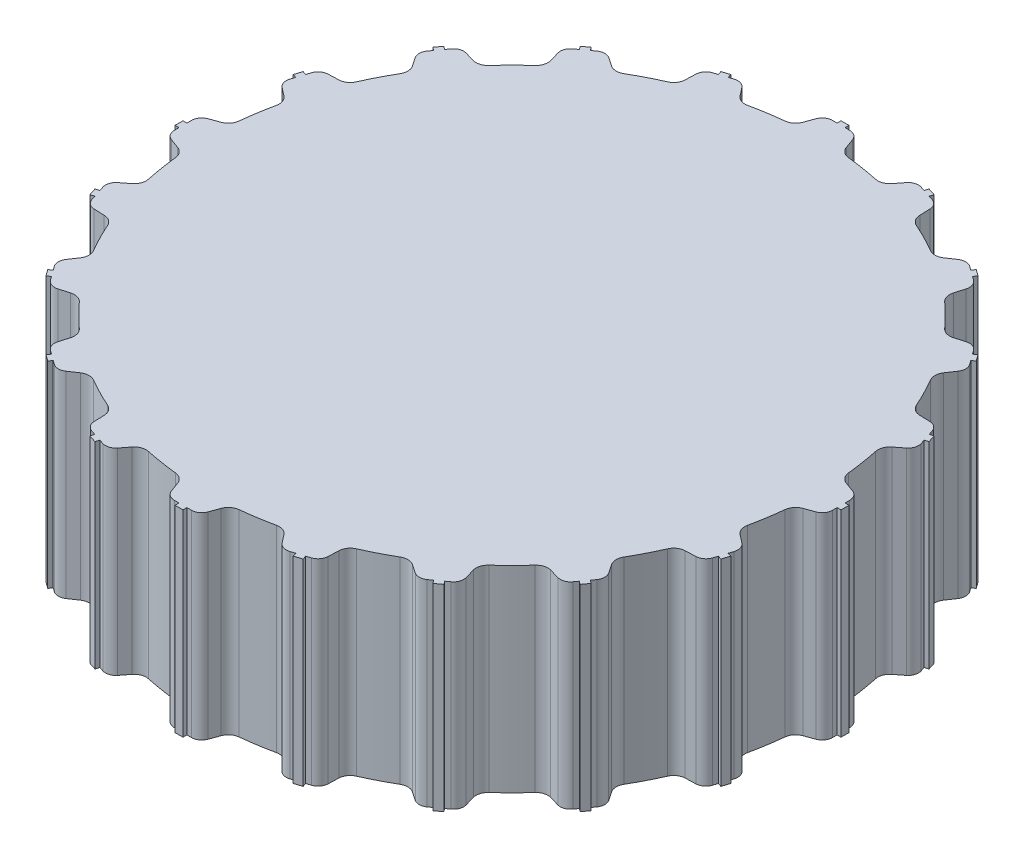
SolidWorks part; units mm, degrees
ref_plane "Front Plane" through (0, 0, 0) normal (0, 0, 1) x (1, 0, 0)
ref_plane "Top Plane" through (0, 0, 0) normal (0, 1, 0) x (1, 0, 0)
ref_plane "Right Plane" through (0, 0, 0) normal (1, 0, 0) x (0, 0, -1)
sketch "Sketch1" plane through (0, 0, 0) normal (0, 1, 0) x (1, 0, 0)
  line L0 (0, 0) -> (0, -23.4605) construction
  line L1 (-0.4359, -16.71) -> (-0.2, -16.71)
  line L2 (0.9245, -16.3679) -> (1.1054, -15.871)
  line L3 (1.2368, -15.51) -> (-2.616, -15.51) construction
  line L4 (0, -15.51) -> (2.4735, -15.51) construction
  line L5 (0.2, -16.71) -> (0.2, -16.91)
  line L6 (0.2, -16.91) -> (-0.2, -16.91)
  line L7 (-0.2, -16.71) -> (-0.2, -16.91)
  line L8 (-0.9245, -16.3679) -> (-1.1054, -15.871)
  line L9 (0.2, -16.71) -> (0.4359, -16.71)
  line L10 (-5.5782, -15.7575) -> (-5.3539, -15.8304)
  line L11 (-5.9372, -15.2811) -> (-5.9557, -14.7526)
  line L12 (-5.3539, -15.8304) -> (-5.4157, -16.0206)
  line L13 (-5.0353, -16.1442) -> (-5.4157, -16.0206)
  line L14 (-4.9735, -15.954) -> (-5.0353, -16.1442)
  line L15 (-4.9735, -15.954) -> (-4.7491, -16.0269)
  line L16 (-4.1787, -15.8524) -> (-3.8531, -15.4358)
  line L17 (-10.1745, -13.2625) -> (-9.9837, -13.4011)
  line L18 (-10.3687, -12.6984) -> (-10.223, -12.1902)
  line L19 (-9.9837, -13.4011) -> (-10.1013, -13.5629)
  line L20 (-9.7776, -13.798) -> (-10.1013, -13.5629)
  line L21 (-9.6601, -13.6362) -> (-9.7776, -13.798)
  line L22 (-9.6601, -13.6362) -> (-9.4692, -13.7749)
  line L23 (-8.8728, -13.7853) -> (-8.4345, -13.4896)
  line L24 (-13.7749, -9.4692) -> (-13.6362, -9.6601)
  line L25 (-13.7853, -8.8728) -> (-13.4896, -8.4345)
  line L26 (-13.6362, -9.6601) -> (-13.798, -9.7776)
  line L27 (-13.5629, -10.1013) -> (-13.798, -9.7776)
  line L28 (-13.4011, -9.9837) -> (-13.5629, -10.1013)
  line L29 (-13.4011, -9.9837) -> (-13.2625, -10.1745)
  line L30 (-12.6984, -10.3687) -> (-12.1902, -10.223)
  line L31 (-16.0269, -4.7491) -> (-15.954, -4.9735)
  line L32 (-15.8524, -4.1787) -> (-15.4358, -3.8531)
  line L33 (-15.954, -4.9735) -> (-16.1442, -5.0353)
  line L34 (-16.0206, -5.4157) -> (-16.1442, -5.0353)
  line L35 (-15.8304, -5.3539) -> (-16.0206, -5.4157)
  line L36 (-15.8304, -5.3539) -> (-15.7575, -5.5782)
  line L37 (-15.2811, -5.9372) -> (-14.7526, -5.9557)
  line L38 (-16.71, 0.4359) -> (-16.71, 0.2)
  line L39 (-16.3679, 0.9245) -> (-15.871, 1.1054)
  line L40 (-16.71, 0.2) -> (-16.91, 0.2)
  line L41 (-16.91, -0.2) -> (-16.91, 0.2)
  line L42 (-16.71, -0.2) -> (-16.91, -0.2)
  line L43 (-16.71, -0.2) -> (-16.71, -0.4359)
  line L44 (-16.3679, -0.9245) -> (-15.871, -1.1054)
  line L45 (-15.7575, 5.5782) -> (-15.8304, 5.3539)
  line L46 (-15.2811, 5.9372) -> (-14.7526, 5.9557)
  line L47 (-15.8304, 5.3539) -> (-16.0206, 5.4157)
  line L48 (-16.1442, 5.0353) -> (-16.0206, 5.4157)
  line L49 (-15.954, 4.9735) -> (-16.1442, 5.0353)
  line L50 (-15.954, 4.9735) -> (-16.0269, 4.7491)
  line L51 (-15.8524, 4.1787) -> (-15.4358, 3.8531)
  line L52 (-13.2625, 10.1745) -> (-13.4011, 9.9837)
  line L53 (-12.6984, 10.3687) -> (-12.1902, 10.223)
  line L54 (-13.4011, 9.9837) -> (-13.5629, 10.1013)
  line L55 (-13.798, 9.7776) -> (-13.5629, 10.1013)
  line L56 (-13.6362, 9.6601) -> (-13.798, 9.7776)
  line L57 (-13.6362, 9.6601) -> (-13.7749, 9.4692)
  line L58 (-13.7853, 8.8728) -> (-13.4896, 8.4345)
  line L59 (-9.4692, 13.7749) -> (-9.6601, 13.6362)
  line L60 (-8.8728, 13.7853) -> (-8.4345, 13.4896)
  line L61 (-9.6601, 13.6362) -> (-9.7776, 13.798)
  line L62 (-10.1013, 13.5629) -> (-9.7776, 13.798)
  line L63 (-9.9837, 13.4011) -> (-10.1013, 13.5629)
  line L64 (-9.9837, 13.4011) -> (-10.1745, 13.2625)
  line L65 (-10.3687, 12.6984) -> (-10.223, 12.1902)
  line L66 (-4.7491, 16.0269) -> (-4.9735, 15.954)
  line L67 (-4.1787, 15.8524) -> (-3.8531, 15.4358)
  line L68 (-4.9735, 15.954) -> (-5.0353, 16.1442)
  line L69 (-5.4157, 16.0206) -> (-5.0353, 16.1442)
  line L70 (-5.3539, 15.8304) -> (-5.4157, 16.0206)
  line L71 (-5.3539, 15.8304) -> (-5.5782, 15.7575)
  line L72 (-5.9372, 15.2811) -> (-5.9557, 14.7526)
  line L73 (0.4359, 16.71) -> (0.2, 16.71)
  line L74 (0.9245, 16.3679) -> (1.1054, 15.871)
  line L75 (0.2, 16.71) -> (0.2, 16.91)
  line L76 (-0.2, 16.91) -> (0.2, 16.91)
  line L77 (-0.2, 16.71) -> (-0.2, 16.91)
  line L78 (-0.2, 16.71) -> (-0.4359, 16.71)
  line L79 (-0.9245, 16.3679) -> (-1.1054, 15.871)
  line L80 (5.5782, 15.7575) -> (5.3539, 15.8304)
  line L81 (5.9372, 15.2811) -> (5.9557, 14.7526)
  line L82 (5.3539, 15.8304) -> (5.4157, 16.0206)
  line L83 (5.0353, 16.1442) -> (5.4157, 16.0206)
  line L84 (4.9735, 15.954) -> (5.0353, 16.1442)
  line L85 (4.9735, 15.954) -> (4.7491, 16.0269)
  line L86 (4.1787, 15.8524) -> (3.8531, 15.4358)
  line L87 (10.1745, 13.2625) -> (9.9837, 13.4011)
  line L88 (10.3687, 12.6984) -> (10.223, 12.1902)
  line L89 (9.9837, 13.4011) -> (10.1013, 13.5629)
  line L90 (9.7776, 13.798) -> (10.1013, 13.5629)
  line L91 (9.6601, 13.6362) -> (9.7776, 13.798)
  line L92 (9.6601, 13.6362) -> (9.4692, 13.7749)
  line L93 (8.8728, 13.7853) -> (8.4345, 13.4896)
  line L94 (13.7749, 9.4692) -> (13.6362, 9.6601)
  line L95 (13.7853, 8.8728) -> (13.4896, 8.4345)
  line L96 (13.6362, 9.6601) -> (13.798, 9.7776)
  line L97 (13.5629, 10.1013) -> (13.798, 9.7776)
  line L98 (13.4011, 9.9837) -> (13.5629, 10.1013)
  line L99 (13.4011, 9.9837) -> (13.2625, 10.1745)
  line L100 (12.6984, 10.3687) -> (12.1902, 10.223)
  line L101 (16.0269, 4.7491) -> (15.954, 4.9735)
  line L102 (15.8524, 4.1787) -> (15.4358, 3.8531)
  line L103 (15.954, 4.9735) -> (16.1442, 5.0353)
  line L104 (16.0206, 5.4157) -> (16.1442, 5.0353)
  line L105 (15.8304, 5.3539) -> (16.0206, 5.4157)
  line L106 (15.8304, 5.3539) -> (15.7575, 5.5782)
  line L107 (15.2811, 5.9372) -> (14.7526, 5.9557)
  line L108 (16.71, -0.4359) -> (16.71, -0.2)
  line L109 (16.3679, -0.9245) -> (15.871, -1.1054)
  line L110 (16.71, -0.2) -> (16.91, -0.2)
  line L111 (16.91, 0.2) -> (16.91, -0.2)
  line L112 (16.71, 0.2) -> (16.91, 0.2)
  line L113 (16.71, 0.2) -> (16.71, 0.4359)
  line L114 (16.3679, 0.9245) -> (15.871, 1.1054)
  line L115 (15.7575, -5.5782) -> (15.8304, -5.3539)
  line L116 (15.2811, -5.9372) -> (14.7526, -5.9557)
  line L117 (15.8304, -5.3539) -> (16.0206, -5.4157)
  line L118 (16.1442, -5.0353) -> (16.0206, -5.4157)
  line L119 (15.954, -4.9735) -> (16.1442, -5.0353)
  line L120 (15.954, -4.9735) -> (16.0269, -4.7491)
  line L121 (15.8524, -4.1787) -> (15.4358, -3.8531)
  line L122 (13.2625, -10.1745) -> (13.4011, -9.9837)
  line L123 (12.6984, -10.3687) -> (12.1902, -10.223)
  line L124 (13.4011, -9.9837) -> (13.5629, -10.1013)
  line L125 (13.798, -9.7776) -> (13.5629, -10.1013)
  line L126 (13.6362, -9.6601) -> (13.798, -9.7776)
  line L127 (13.6362, -9.6601) -> (13.7749, -9.4692)
  line L128 (13.7853, -8.8728) -> (13.4896, -8.4345)
  line L129 (9.4692, -13.7749) -> (9.6601, -13.6362)
  line L130 (8.8728, -13.7853) -> (8.4345, -13.4896)
  line L131 (9.6601, -13.6362) -> (9.7776, -13.798)
  line L132 (10.1013, -13.5629) -> (9.7776, -13.798)
  line L133 (9.9837, -13.4011) -> (10.1013, -13.5629)
  line L134 (9.9837, -13.4011) -> (10.1745, -13.2625)
  line L135 (10.3687, -12.6984) -> (10.223, -12.1902)
  line L136 (4.7491, -16.0269) -> (4.9735, -15.954)
  line L137 (4.1787, -15.8524) -> (3.8531, -15.4358)
  line L138 (4.9735, -15.954) -> (5.0353, -16.1442)
  line L139 (5.4157, -16.0206) -> (5.0353, -16.1442)
  line L140 (5.3539, -15.8304) -> (5.4157, -16.0206)
  line L141 (5.3539, -15.8304) -> (5.5782, -15.7575)
  line L142 (5.9372, -15.2811) -> (5.9557, -14.7526)
  arc A2 (1.6121, -15.4755) -> (3.249, -15.2162) centre (0, 0) ccw
  arc A3 (0.9245, -16.3679) -> (0.4359, -16.71) centre (0.4359, -16.19) cw
  arc A4 (1.6121, -15.4755) -> (1.1054, -15.871) centre (1.6748, -16.0782) ccw
  arc A5 (-1.6121, -15.4755) -> (-1.1054, -15.871) centre (-1.6748, -16.0782) cw
  arc A6 (-0.9245, -16.3679) -> (-0.4359, -16.71) centre (-0.4359, -16.19) ccw
  arc A7 (-5.9372, -15.2811) -> (-5.5782, -15.7575) centre (-5.4175, -15.2629) ccw
  arc A8 (-6.3153, -14.2199) -> (-5.9557, -14.7526) centre (-6.5613, -14.7738) cw
  arc A9 (-4.1787, -15.8524) -> (-4.7491, -16.0269) centre (-4.5884, -15.5323) cw
  arc A10 (-3.249, -15.2162) -> (-3.8531, -15.4358) centre (-3.3756, -15.8089) ccw
  arc A11 (-10.3687, -12.6984) -> (-10.1745, -13.2625) centre (-9.8689, -12.8418) ccw
  arc A12 (-10.4004, -11.5724) -> (-10.223, -12.1902) centre (-10.8055, -12.0231) cw
  arc A13 (-8.8728, -13.7853) -> (-9.4692, -13.7749) centre (-9.1636, -13.3542) cw
  arc A14 (-7.7921, -13.4675) -> (-8.4345, -13.4896) centre (-8.0956, -13.992) ccw
  arc A15 (-13.7853, -8.8728) -> (-13.7749, -9.4692) centre (-13.3542, -9.1636) ccw
  arc A16 (-13.4675, -7.7921) -> (-13.4896, -8.4345) centre (-13.992, -8.0956) cw
  arc A17 (-12.6984, -10.3687) -> (-13.2625, -10.1745) centre (-12.8418, -9.8689) cw
  arc A18 (-11.5724, -10.4004) -> (-12.1902, -10.223) centre (-12.0231, -10.8055) ccw
  arc A19 (-15.8524, -4.1787) -> (-16.0269, -4.7491) centre (-15.5323, -4.5884) ccw
  arc A20 (-15.2162, -3.249) -> (-15.4358, -3.8531) centre (-15.8089, -3.3756) cw
  arc A21 (-15.2811, -5.9372) -> (-15.7575, -5.5782) centre (-15.2629, -5.4175) cw
  arc A22 (-14.2199, -6.3153) -> (-14.7526, -5.9557) centre (-14.7738, -6.5613) ccw
  arc A23 (-16.3679, 0.9245) -> (-16.71, 0.4359) centre (-16.19, 0.4359) ccw
  arc A24 (-15.4755, 1.6121) -> (-15.871, 1.1054) centre (-16.0782, 1.6748) cw
  arc A25 (-16.3679, -0.9245) -> (-16.71, -0.4359) centre (-16.19, -0.4359) cw
  arc A26 (-15.4755, -1.6121) -> (-15.871, -1.1054) centre (-16.0782, -1.6748) ccw
  arc A27 (-15.2811, 5.9372) -> (-15.7575, 5.5782) centre (-15.2629, 5.4175) ccw
  arc A28 (-14.2199, 6.3153) -> (-14.7526, 5.9557) centre (-14.7738, 6.5613) cw
  arc A29 (-15.8524, 4.1787) -> (-16.0269, 4.7491) centre (-15.5323, 4.5884) cw
  arc A30 (-15.2162, 3.249) -> (-15.4358, 3.8531) centre (-15.8089, 3.3756) ccw
  arc A31 (-12.6984, 10.3687) -> (-13.2625, 10.1745) centre (-12.8418, 9.8689) ccw
  arc A32 (-11.5724, 10.4004) -> (-12.1902, 10.223) centre (-12.0231, 10.8055) cw
  arc A33 (-13.7853, 8.8728) -> (-13.7749, 9.4692) centre (-13.3542, 9.1636) cw
  arc A34 (-13.4675, 7.7921) -> (-13.4896, 8.4345) centre (-13.992, 8.0956) ccw
  arc A35 (-8.8728, 13.7853) -> (-9.4692, 13.7749) centre (-9.1636, 13.3542) ccw
  arc A36 (-7.7921, 13.4675) -> (-8.4345, 13.4896) centre (-8.0956, 13.992) cw
  arc A37 (-10.3687, 12.6984) -> (-10.1745, 13.2625) centre (-9.8689, 12.8418) cw
  arc A38 (-10.4004, 11.5724) -> (-10.223, 12.1902) centre (-10.8055, 12.0231) ccw
  arc A39 (-4.1787, 15.8524) -> (-4.7491, 16.0269) centre (-4.5884, 15.5323) ccw
  arc A40 (-3.249, 15.2162) -> (-3.8531, 15.4358) centre (-3.3756, 15.8089) cw
  arc A41 (-5.9372, 15.2811) -> (-5.5782, 15.7575) centre (-5.4175, 15.2629) cw
  arc A42 (-6.3153, 14.2199) -> (-5.9557, 14.7526) centre (-6.5613, 14.7738) ccw
  arc A43 (0.9245, 16.3679) -> (0.4359, 16.71) centre (0.4359, 16.19) ccw
  arc A44 (1.6121, 15.4755) -> (1.1054, 15.871) centre (1.6748, 16.0782) cw
  arc A45 (-0.9245, 16.3679) -> (-0.4359, 16.71) centre (-0.4359, 16.19) cw
  arc A46 (-1.6121, 15.4755) -> (-1.1054, 15.871) centre (-1.6748, 16.0782) ccw
  arc A47 (5.9372, 15.2811) -> (5.5782, 15.7575) centre (5.4175, 15.2629) ccw
  arc A48 (6.3153, 14.2199) -> (5.9557, 14.7526) centre (6.5613, 14.7738) cw
  arc A49 (4.1787, 15.8524) -> (4.7491, 16.0269) centre (4.5884, 15.5323) cw
  arc A50 (3.249, 15.2162) -> (3.8531, 15.4358) centre (3.3756, 15.8089) ccw
  arc A51 (10.3687, 12.6984) -> (10.1745, 13.2625) centre (9.8689, 12.8418) ccw
  arc A52 (10.4004, 11.5724) -> (10.223, 12.1902) centre (10.8055, 12.0231) cw
  arc A53 (8.8728, 13.7853) -> (9.4692, 13.7749) centre (9.1636, 13.3542) cw
  arc A54 (7.7921, 13.4675) -> (8.4345, 13.4896) centre (8.0956, 13.992) ccw
  arc A55 (13.7853, 8.8728) -> (13.7749, 9.4692) centre (13.3542, 9.1636) ccw
  arc A56 (13.4675, 7.7921) -> (13.4896, 8.4345) centre (13.992, 8.0956) cw
  arc A57 (12.6984, 10.3687) -> (13.2625, 10.1745) centre (12.8418, 9.8689) cw
  arc A58 (11.5724, 10.4004) -> (12.1902, 10.223) centre (12.0231, 10.8055) ccw
  arc A59 (15.8524, 4.1787) -> (16.0269, 4.7491) centre (15.5323, 4.5884) ccw
  arc A60 (15.2162, 3.249) -> (15.4358, 3.8531) centre (15.8089, 3.3756) cw
  arc A61 (15.2811, 5.9372) -> (15.7575, 5.5782) centre (15.2629, 5.4175) cw
  arc A62 (14.2199, 6.3153) -> (14.7526, 5.9557) centre (14.7738, 6.5613) ccw
  arc A63 (16.3679, -0.9245) -> (16.71, -0.4359) centre (16.19, -0.4359) ccw
  arc A64 (15.4755, -1.6121) -> (15.871, -1.1054) centre (16.0782, -1.6748) cw
  arc A65 (16.3679, 0.9245) -> (16.71, 0.4359) centre (16.19, 0.4359) cw
  arc A66 (15.4755, 1.6121) -> (15.871, 1.1054) centre (16.0782, 1.6748) ccw
  arc A67 (15.2811, -5.9372) -> (15.7575, -5.5782) centre (15.2629, -5.4175) ccw
  arc A68 (14.2199, -6.3153) -> (14.7526, -5.9557) centre (14.7738, -6.5613) cw
  arc A69 (15.8524, -4.1787) -> (16.0269, -4.7491) centre (15.5323, -4.5884) cw
  arc A70 (15.2162, -3.249) -> (15.4358, -3.8531) centre (15.8089, -3.3756) ccw
  arc A71 (12.6984, -10.3687) -> (13.2625, -10.1745) centre (12.8418, -9.8689) ccw
  arc A72 (11.5724, -10.4004) -> (12.1902, -10.223) centre (12.0231, -10.8055) cw
  arc A73 (13.7853, -8.8728) -> (13.7749, -9.4692) centre (13.3542, -9.1636) cw
  arc A74 (13.4675, -7.7921) -> (13.4896, -8.4345) centre (13.992, -8.0956) ccw
  arc A75 (8.8728, -13.7853) -> (9.4692, -13.7749) centre (9.1636, -13.3542) ccw
  arc A76 (7.7921, -13.4675) -> (8.4345, -13.4896) centre (8.0956, -13.992) cw
  arc A77 (10.3687, -12.6984) -> (10.1745, -13.2625) centre (9.8689, -12.8418) cw
  arc A78 (10.4004, -11.5724) -> (10.223, -12.1902) centre (10.8055, -12.0231) ccw
  arc A79 (4.1787, -15.8524) -> (4.7491, -16.0269) centre (4.5884, -15.5323) ccw
  arc A80 (3.249, -15.2162) -> (3.8531, -15.4358) centre (3.3756, -15.8089) cw
  arc A81 (5.9372, -15.2811) -> (5.5782, -15.7575) centre (5.4175, -15.2629) cw
  arc A82 (6.3153, -14.2199) -> (5.9557, -14.7526) centre (6.5613, -14.7738) ccw
  arc A83 (6.3153, -14.2199) -> (7.7921, -13.4675) centre (0, 0) ccw
  arc A84 (10.4004, -11.5724) -> (11.5724, -10.4004) centre (0, 0) ccw
  arc A85 (13.4675, -7.7921) -> (14.2199, -6.3153) centre (0, 0) ccw
  arc A86 (15.2162, -3.249) -> (15.4755, -1.6121) centre (0, 0) ccw
  arc A87 (15.4755, 1.6121) -> (15.2162, 3.249) centre (0, 0) ccw
  arc A88 (14.2199, 6.3153) -> (13.4675, 7.7921) centre (0, 0) ccw
  arc A89 (11.5724, 10.4004) -> (10.4004, 11.5724) centre (0, 0) ccw
  arc A90 (7.7921, 13.4675) -> (6.3153, 14.2199) centre (0, 0) ccw
  arc A91 (3.249, 15.2162) -> (1.6121, 15.4755) centre (0, 0) ccw
  arc A92 (-1.6121, 15.4755) -> (-3.249, 15.2162) centre (0, 0) ccw
  arc A93 (-6.3153, 14.2199) -> (-7.7921, 13.4675) centre (0, 0) ccw
  arc A94 (-10.4004, 11.5724) -> (-11.5724, 10.4004) centre (0, 0) ccw
  arc A95 (-13.4675, 7.7921) -> (-14.2199, 6.3153) centre (0, 0) ccw
  arc A96 (-15.2162, 3.249) -> (-15.4755, 1.6121) centre (0, 0) ccw
  arc A97 (-15.4755, -1.6121) -> (-15.2162, -3.249) centre (0, 0) ccw
  arc A98 (-14.2199, -6.3153) -> (-13.4675, -7.7921) centre (0, 0) ccw
  arc A99 (-11.5724, -10.4004) -> (-10.4004, -11.5724) centre (0, 0) ccw
  arc A100 (-7.7921, -13.4675) -> (-6.3153, -14.2199) centre (0, 0) ccw
  arc A101 (-3.249, -15.2162) -> (-1.6121, -15.4755) centre (0, 0) ccw
  point P3 (-0.8, -16.71)
  point P18 (0.8, -16.71)
  point P26 (0, -16.91)
  point P27 (0, -16.71)
  dimension "D1" = 20
  dimension "D7" = 0.52
  dimension "D2" = 20
  dimension "D3" = 1.2
  dimension "D4" = 0.2
  dimension "D5" = 0.2
  dimension "D6" = 0.8
extrude "Boss-Extrude1" add sketch "Sketch1" along normal blind 10
